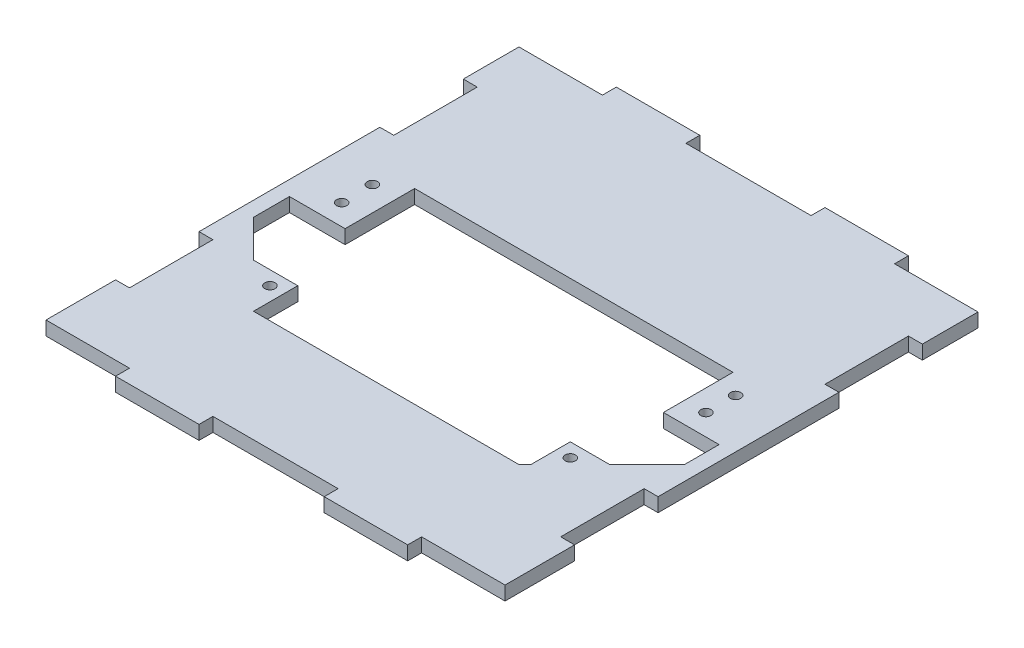
SolidWorks part; units mm, degrees
ref_plane "Front Plane" through (0, 0, 0) normal (0, 0, 1) x (1, 0, 0)
ref_plane "Top Plane" through (0, 0, 0) normal (0, 1, 0) x (1, 0, 0)
ref_plane "Right Plane" through (0, 0, 0) normal (1, 0, 0) x (0, 0, -1)
sketch "Sketch1" plane through (0, 0, 0) normal (0, 1, 0) x (1, 0, 0)
  line L0 (-42.4542, 51.3615) -> (-72.4542, 51.3615)
  line L1 (62.5458, 51.3615) -> (92.5458, 51.3615)
  line L2 (-72.4542, 51.3615) -> (-72.4542, -118.6385)
  line L3 (-72.4542, -118.6385) -> (-42.4542, -118.6385)
  line L4 (92.5458, 51.3615) -> (92.5458, -118.6385)
  line L5 (-72.4542, 31.3615) -> (-67.4542, 31.3615)
  line L6 (-72.4542, 31.3615) -> (-72.4542, 1.3615)
  line L7 (-72.4542, 1.3615) -> (-67.4542, 1.3615)
  line L8 (-67.4542, 31.3615) -> (-67.4542, 1.3615)
  line L9 (-72.4542, -63.6385) -> (-67.4542, -63.6385)
  line L10 (-72.4542, -63.6385) -> (-72.4542, -93.6385)
  line L11 (-72.4542, -93.6385) -> (-67.4542, -93.6385)
  line L12 (-67.4542, -63.6385) -> (-67.4542, -93.6385)
  line L13 (92.5458, 31.3615) -> (87.5458, 31.3615)
  line L14 (92.5458, 31.3615) -> (92.5458, 1.3615)
  line L15 (92.5458, 1.3615) -> (87.5458, 1.3615)
  line L16 (87.5458, 31.3615) -> (87.5458, 1.3615)
  line L17 (92.5458, -63.6385) -> (87.5458, -63.6385)
  line L18 (92.5458, -63.6385) -> (92.5458, -93.6385)
  line L19 (92.5458, -93.6385) -> (87.5458, -93.6385)
  line L20 (87.5458, -63.6385) -> (87.5458, -93.6385)
  line L22 (-42.4542, -118.6385) -> (-42.4542, -123.6385)
  line L23 (-42.4542, -123.6385) -> (-12.4542, -123.6385)
  line L24 (-12.4542, -118.6385) -> (-12.4542, -123.6385)
  line L26 (32.5458, -118.6385) -> (32.5458, -123.6385)
  line L27 (32.5458, -123.6385) -> (62.5458, -123.6385)
  line L28 (62.5458, -118.6385) -> (62.5458, -123.6385)
  line L29 (62.5458, -118.6385) -> (92.5458, -118.6385)
  line L30 (-12.4542, -118.6385) -> (32.5458, -118.6385)
  line L33 (-12.4542, 51.3615) -> (32.5458, 51.3615)
  line L37 (62.5458, 51.3615) -> (92.5458, 51.3615)
  line L39 (62.5458, 51.3615) -> (62.5458, 56.3615)
  line L40 (62.5458, 56.3615) -> (32.5458, 56.3615)
  line L41 (32.5458, 51.3615) -> (32.5458, 56.3615)
  line L43 (-12.4542, 51.3615) -> (-12.4542, 56.3615)
  line L44 (-12.4542, 56.3615) -> (-42.4542, 56.3615)
  line L45 (-42.4542, 51.3615) -> (-42.4542, 56.3615)
  dimension "D3" = 30
  dimension "D4" = 5
  dimension "D5" = 30
  dimension "D6" = 30
  dimension "D7" = 30
  dimension "D8" = 5
  dimension "D9" = 5
  dimension "D10" = 5
  dimension "D11" = 50
  dimension "D12" = 50
  dimension "D13" = 55
  dimension "D14" = 55
  dimension "D15" = 30
  dimension "D16" = 30
  dimension "D17" = 30
  dimension "D18" = 30
  dimension "D19" = 165
  dimension "D20" = 30
  dimension "D21" = 30
  dimension "D22" = 65
  dimension "D23" = 5
  dimension "D24" = 5
  dimension "D25" = 30
  dimension "D26" = 30
  dimension "D27" = 5
  dimension "D28" = 5
  dimension "D29" = 65
extrude "Boss-Extrude1" add sketch "Sketch1" along normal blind 5 contours L20 L17 L4 L15 L16 L13 L1 L2 L5 L8 L7 L9 L12 L11 L3 L19
sketch "Sketch3" plane through (0, 5, 0) normal (0, 1, 0) x (1, 0, 0)
  line L0 (87.2958, -11.4555) -> (87.2958, -48.9205)
  line L1 (87.2958, -48.9205) -> (57.5778, -78.6385)
  line L2 (57.5778, -78.6385) -> (-37.7992, -78.6385)
  line L3 (-67.1362, -49.3015) -> (-37.7992, -78.6385)
  line L4 (-67.1362, -49.3015) -> (-67.1362, -11.4555)
  line L5 (-67.1362, -11.4555) -> (87.2958, -11.4555)
  line L6 (87.2958, -36.4555) -> (67.2958, -36.4555)
  line L7 (67.2958, -36.4555) -> (67.2958, -11.4555)
  line L8 (-47.1362, -11.4555) -> (-47.1362, -36.4555)
  line L9 (-47.1362, -36.4555) -> (-67.1362, -36.4555)
  line L10 (-72.4542, -118.6385) -> (-42.4542, -118.6385) construction
  line L13 (92.5458, 1.3615) -> (92.5458, -63.6385) construction
  line L15 (-37.8792, -78.5585) -> (-37.8792, -62.7165)
  line L16 (-37.8792, -62.7165) -> (-53.7212, -62.7165)
  line L17 (73.8808, -62.3355) -> (59.6898, -62.3355)
  line L18 (59.6898, -62.3355) -> (59.6898, -76.5265)
  circle A0 centre (74.9768, -28.8545) radius 1.854
  circle A1 centre (74.9768, -18.1865) radius 1.854
  circle A2 centre (64.6898, -67.3355) radius 1.854
  circle A3 centre (-42.8792, -67.7165) radius 1.854
  circle A4 centre (-55.9602, -17.8055) radius 1.854
  circle A5 centre (-55.8332, -28.9815) radius 1.854
  dimension "D14" = 3.708
  dimension "D15" = 3.708
  dimension "D16" = 3.708
  dimension "D19" = 3.708
  dimension "D22" = 3.708
  dimension "D23" = 3.708
  dimension "D1" = 41.4888
  dimension "D2" = 37.846
  dimension "D3" = 37.465
  dimension "D4" = 42.0276
  dimension "D5" = 95.377
  dimension "D6" = 12.319
  dimension "D7" = 12.319
  dimension "D8" = 6.731
  dimension "D9" = 17.399
  dimension "D10" = 6.35
  dimension "D11" = 11.176
  dimension "D12" = 11.303
  dimension "D13" = 17.526
  dimension "D17" = 24.257
  dimension "D18" = 10.922
  dimension "D20" = 11.303
  dimension "D21" = 22.606
  dimension "D24" = 20
  dimension "D25" = 25
  dimension "D26" = 20
  dimension "D27" = 25
  dimension "D28" = 40
  dimension "D29" = 5.25
  dimension "D30" = 5
  dimension "D31" = 5
  dimension "D32" = 5
  dimension "D33" = 5
  dimension "D35" = 14.191
  dimension "D36" = 14.191
  dimension "D37" = 15.842
  dimension "D38" = 15.842
  dimension "D39" = 25
  dimension "D40" = 25
extrude "Cut-Extrude1" cut sketch "Sketch3" against normal blind 10 contours L18 L17 L1 L0 L6 L7 L5 L8 L9 L4 L3 L16 L15 L2 | A3 | A4 | A5 | A2 | A1 | A0
